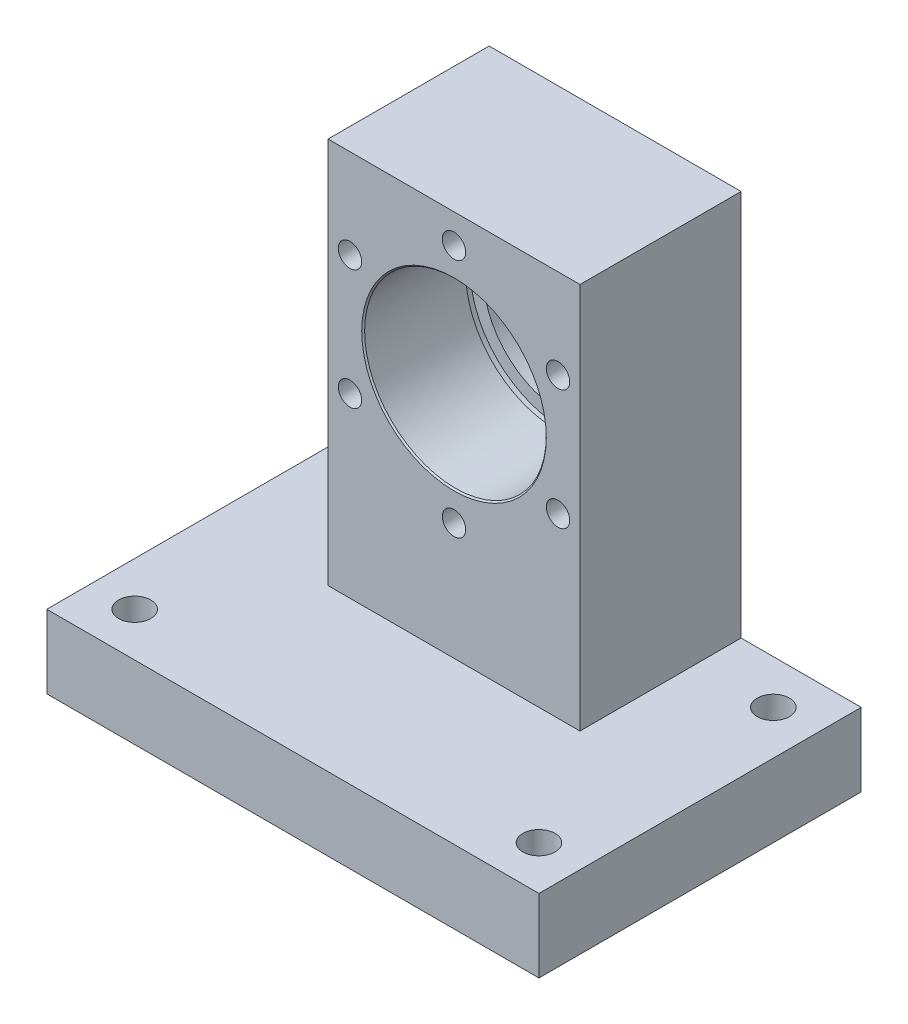
SolidWorks part; units mm, degrees
ref_plane "前视基准面" through (0, 0, 0) normal (0, 0, 1) x (1, 0, 0)
ref_plane "上视基准面" through (0, 0, 0) normal (0, 1, 0) x (1, 0, 0)
ref_plane "右视基准面" through (0, 0, 0) normal (1, 0, 0) x (0, 0, -1)
other "Configuration Table"
sketch "草图1" plane through (0, 0, 0) normal (0, 1, 0) x (1, 0, 0)
  line L1 (0, 0) -> (168, 0)
  line L2 (0, 0) -> (0, 110)
  line L3 (0, 110) -> (168, 110)
  line L4 (168, 0) -> (168, 110)
  dimension "D1" = 110
  dimension "D2" = 168
extrude "凸台-拉伸1" add sketch "草图1" along normal blind 25
sketch "草图2" plane through (0, 25, 0) normal (0, 1, 0) x (1, 0, 0)
  line L0 (84, 0) -> (84, 110) construction
  line L1 (0, 0) -> (168, 0) construction
  line L2 (168, 110) -> (0, 110) construction
  line L3 (0, 55) -> (168, 55) construction
  line L4 (0, 110) -> (0, 0) construction
  line L5 (168, 0) -> (168, 110) construction
  circle A0 centre (15, 95) radius 5.5
  circle A1 centre (153, 95) radius 5.5
  circle A2 centre (153, 15) radius 5.5
  circle A3 centre (15, 15) radius 5.5
  dimension "D3" = 11
  dimension "D1" = 15
  dimension "D2" = 138
extrude "切除-拉伸1" cut sketch "草图2" against normal through all
sketch "草图3" plane through (0, 25, 0) normal (0, 1, 0) x (1, 0, 0)
  line L0 (84, 110) -> (84, 0) construction
  line L1 (168, 110) -> (0, 110) construction
  line L2 (0, 0) -> (168, 0) construction
  line L3 (0, 55) -> (168, 55) construction
  line L4 (0, 110) -> (0, 0) construction
  line L5 (168, 0) -> (168, 110) construction
  line L6 (127, 110) -> (127, 55)
  line L7 (127, 110) -> (41, 110)
  line L9 (127, 55) -> (41, 55)
  line L10 (41, 110) -> (41, 55)
  dimension "D1" = 86
  dimension "D2" = 55
extrude "凸台-拉伸2" add sketch "草图3" along normal blind 132
sketch "草图4" plane through (0, 0, -55) normal (0, 0, 1) x (1, 0, 0)
  line L0 (84, 25) -> (84, 157) construction
  line L1 (41, 25) -> (127, 25) construction
  line L2 (41, 157) -> (127, 157) construction
  circle A0 centre (84, 106) radius 31
  dimension "D1" = 62
  dimension "D2" = 81
extrude "切除-拉伸2" cut sketch "草图4" against normal blind 35
chamfer "倒角1" distance 0.5 angle 45 1 edges at (115, 106, -55)
sketch "草图10" plane through (0, 0, -90) normal (0, 0, 1) x (1, 0, 0)
  circle A0 centre (84, 106) radius 27
  dimension "D1" = 54
sketch "草图11" plane through (0, 0, -55) normal (0, 0, 1) x (1, 0, 0)
  line L0 (84, 157) -> (84, 25) construction
  line L1 (41, 157) -> (127, 157) construction
  line L2 (0, 25) -> (168, 25) construction
  circle A1 centre (84, 106) radius 41 construction
  dimension "D1" = 82
  dimension "D2" = 132
sketch "草图18" plane through (0, 0, -55) normal (0, 0, 1) x (1, 0, 0)
  line L0 (84, 157) -> (84, 25) construction
  circle A0 centre (84, 106) radius 41 construction
  point P0 (84, 147)
  point P6 (84, 65)
  point P8 (55.2403, 135.2212)
  point P10 (55.2403, 76.7788)
sketch "草图24" plane through (0, 0, -110) normal (0, 0, -1) x (-1, 0, 0)
  circle A0 centre (-84, 106) radius 27
  dimension "D1" = 54
extrude "切除-拉伸6" cut sketch "草图24" against normal blind 18
sketch "草图25" plane through (0, 0, -92) normal (0, 0, -1) x (-1, 0, 0)
  circle A0 centre (-84, 106) radius 31.5
  dimension "D1" = 63
extrude "切除-拉伸7" cut sketch "草图25" against normal blind 2
sketch "草图26" plane through (0, 0, -55) normal (0, 0, 1) x (1, 0, 0)
  circle A1 centre (84, 147) radius 4
  circle A2 centre (119.507, 126.5) radius 4
  circle A3 centre (119.507, 85.5) radius 4
  circle A4 centre (84, 65) radius 4
  circle A5 centre (48.493, 85.5) radius 4
  circle A6 centre (48.493, 126.5) radius 4
  point P18 (84, 106)
  dimension "D2" = 8
  dimension "D3" = 6
extrude "切除-拉伸8" cut sketch "草图26" against normal blind 21
